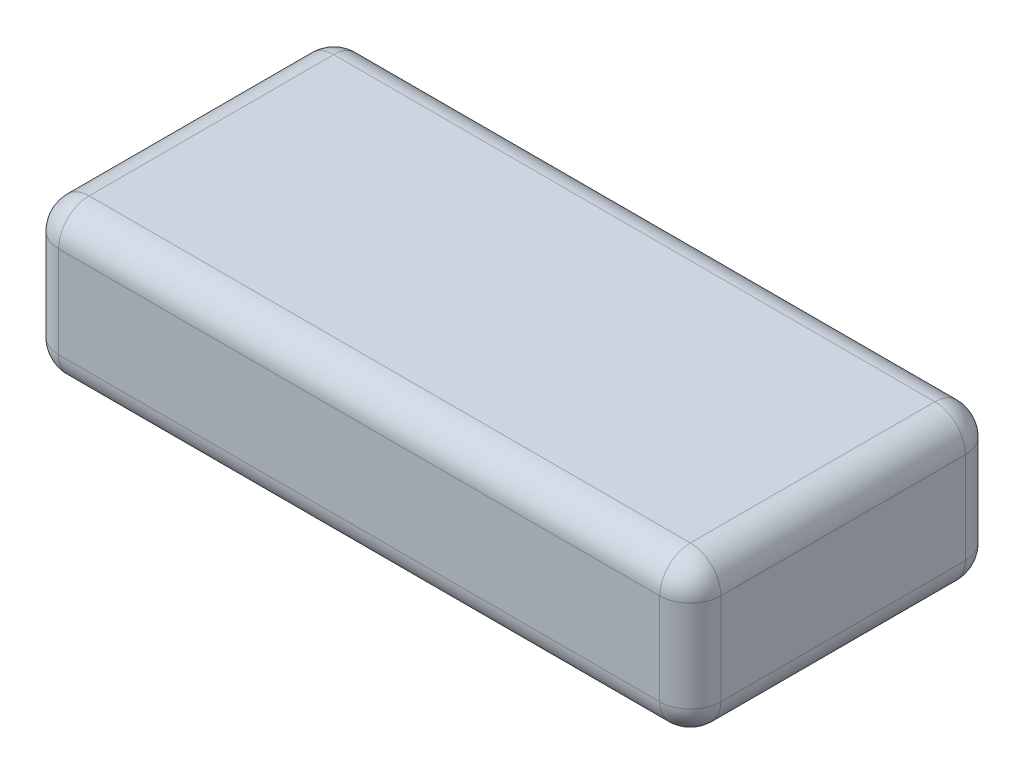
SolidWorks part; units mm, degrees
ref_plane "Front Plane" through (0, 0, 0) normal (0, 0, 1) x (1, 0, 0)
ref_plane "Top Plane" through (0, 0, 0) normal (0, 1, 0) x (1, 0, 0)
ref_plane "Right Plane" through (0, 0, 0) normal (1, 0, 0) x (0, 0, -1)
sketch "Sketch1" plane through (0, 0, 0) normal (0, 1, 0) x (1, 0, 0)
  line L1 (-32.5, -15) -> (32.5, -15)
  line L2 (-32.5, -15) -> (-32.5, 15)
  line L3 (-32.5, 15) -> (32.5, 15)
  line L4 (32.5, -15) -> (32.5, 15)
  line L5 (-32.5, -15) -> (32.5, 15) construction
  line L6 (-32.5, 15) -> (32.5, -15) construction
  point P0 (0, 0)
  dimension "D1" = 65
  dimension "D2" = 30
extrude "Boss-Extrude1" add sketch "Sketch1" along normal blind 15
fillet "Fillet1" radius 3 12 edges at (0, 15, 15) (-32.5, 15, 0) (0, 15, -15) (32.5, 15, 0) (0, 0, -15) (-32.5, 0, 0) (0, 0, 15) (32.5, 0, 0) (32.5, 7.5, -15) (-32.5, 7.5, -15) (-32.5, 7.5, 15) (32.5, 7.5, 15)
